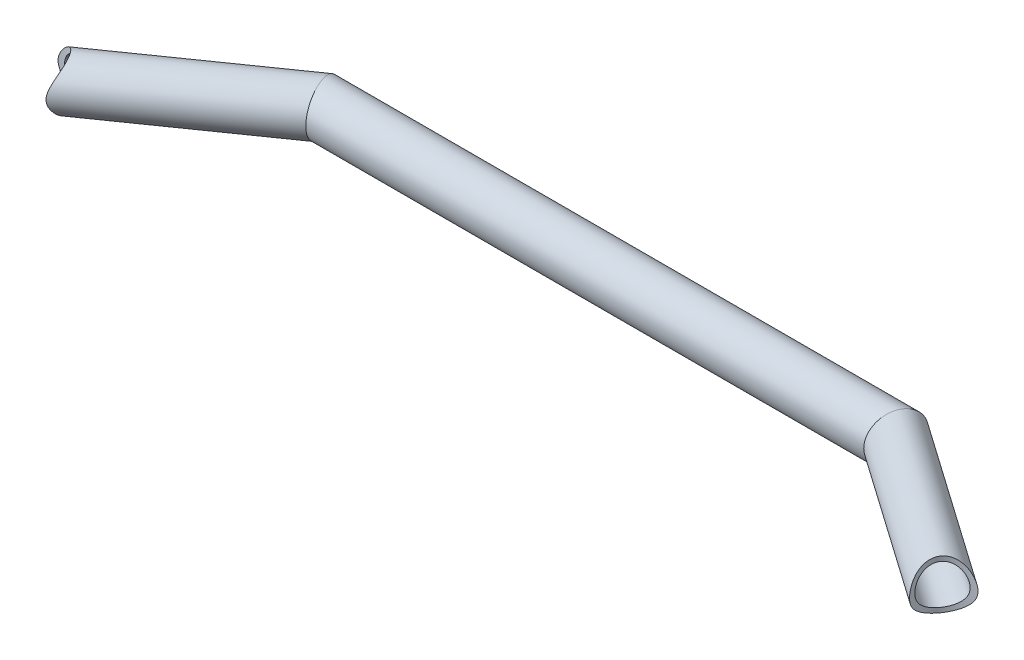
SolidWorks part; units mm, degrees
material "AISI 1020"
ref_plane "Plano frontal" through (0, 0, 0) normal (0, 0, 1) x (1, 0, 0)
ref_plane "Plano superior" through (0, 0, 0) normal (0, 1, 0) x (1, 0, 0)
ref_plane "Plano direito" through (0, 0, 0) normal (1, 0, 0) x (0, 0, -1)
sketch "Esboço1" plane through (0, 0, 0) normal (0, 1, 0) x (1, 0, 0)
  line L0 (0, 0) -> (-122.5, 0)
  line L1 (-122.5, 0) -> (-190.5, -47.6141)
  dimension "D1" = 122.5
  dimension "D2" = 145
  dimension "D3" = 68
sketch "Esboço2" plane through (0, 0, 0) normal (1, 0, 0) x (0, 0, -1)
  circle A0 centre (0, 0) radius 10.5
  circle A1 centre (0, 0) radius 8.5
  dimension "D1" = 21
  dimension "D2" = 2
sweep "Varredura1" add profiles "Esboço2" path "Esboço1"
mirror "Espelhar1" about plane through (0, 0, 0) normal (1, 0, 0) of "Varredura1"
sketch "Esboço3" plane through (0, 0, 0) normal (0, 1, 0) x (1, 0, 0)
  line L2 (0, 0) -> (0, 77.0945) construction
  circle A1 centre (196.3522, -51.7119) radius 12.7
  circle A2 centre (-196.3522, -51.7119) radius 12.7
  dimension "D1" = 25.4
extrude "Corte-extrusão1" cut sketch "Esboço3" against normal through all both and the other way through all
